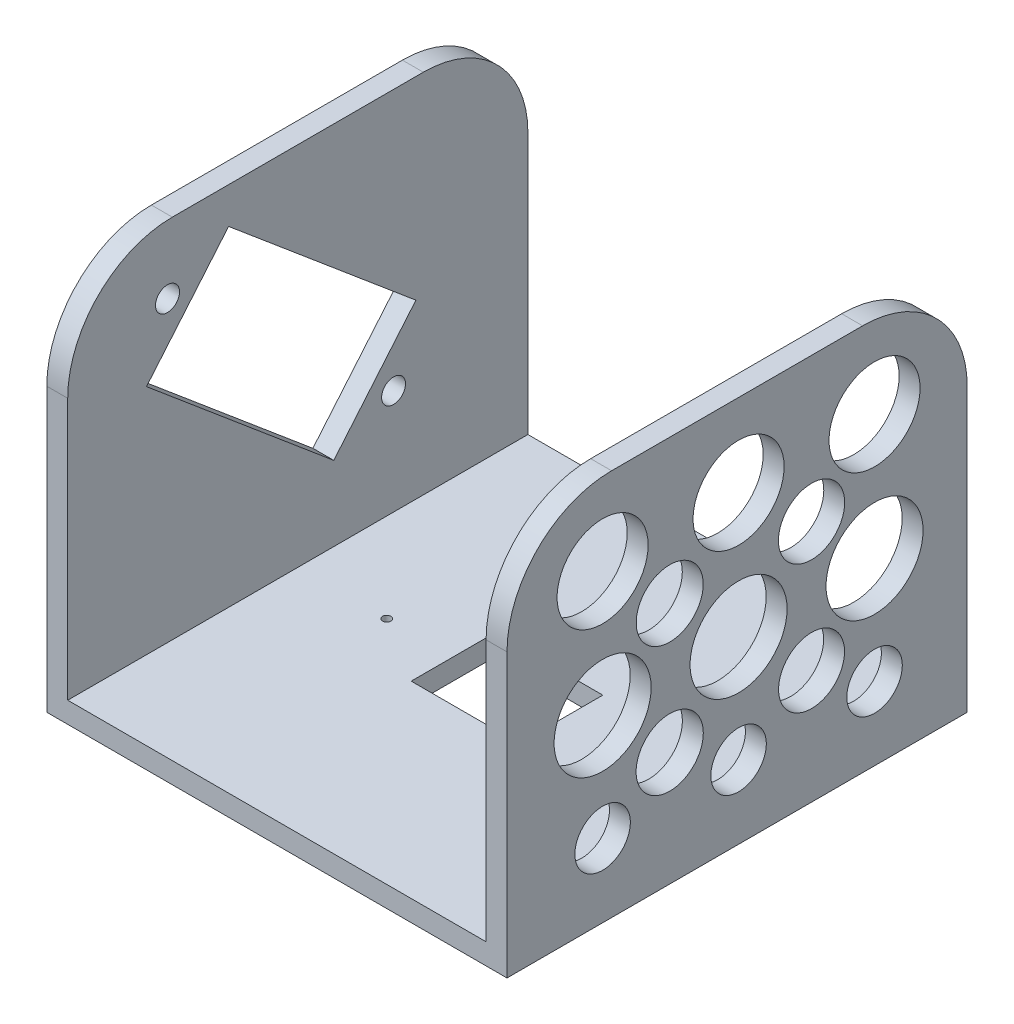
SolidWorks part; units mm, degrees
ref_plane "Front Plane" through (0, 0, 0) normal (0, 0, 1) x (1, 0, 0)
ref_plane "Top Plane" through (0, 0, 0) normal (0, 1, 0) x (1, 0, 0)
ref_plane "Right Plane" through (0, 0, 0) normal (1, 0, 0) x (0, 0, -1)
sketch "Sketch2" plane through (0, 0, 0) normal (0, 1, 0) x (1, 0, 0)
  line L1 (-22, 22) -> (22, 22)
  line L2 (-22, 22) -> (-22, -22)
  line L3 (-22, -22) -> (22, -22)
  line L4 (22, 22) -> (22, -22)
  line L5 (-22, 22) -> (22, -22) construction
  line L6 (-22, -22) -> (22, 22) construction
  point P0 (0, 0)
  dimension "D1" = 44
  dimension "D2" = 44
extrude "Boss-Extrude1" add sketch "Sketch2" along normal blind 2
sketch "Sketch4" plane through (0, 0, 0) normal (0, -1, 0) x (1, 0, 0)
  line L1 (-5.1594, 4) -> (5.1594, 4)
  line L2 (-5.1594, 4) -> (-5.1594, -4)
  line L3 (-5.1594, -4) -> (5.1594, -4)
  line L4 (5.1594, 4) -> (5.1594, -4)
  line L5 (-5.1594, 4) -> (5.1594, -4) construction
  line L6 (-5.1594, -4) -> (5.1594, 4) construction
  point P0 (0, 0)
  dimension "D1" = 10.3187
  dimension "D2" = 8
extrude "Cut-Extrude1" cut sketch "Sketch4" against normal through all
sketch "Sketch5" plane through (0, 0, 0) normal (0, -1, 0) x (1, 0, 0)
  circle A0 centre (-11.5, 0) radius 0.4
  dimension "D1" = 0.8
  dimension "D2" = 11.5
extrude "Cut-Extrude2" cut sketch "Sketch5" against normal blind 3
mirror "Mirror1" about plane through (0, 0, 0) normal (1, 0, 0) of "Cut-Extrude2"
sketch "Sketch8" plane through (0, 2, 0) normal (0, 1, 0) x (1, 0, 0)
  line L0 (-22, -22) -> (22, -22) construction
  line L1 (-22, 22) -> (-20, 22)
  line L2 (-22, 22) -> (-22, -22)
  line L3 (-22, -22) -> (-20, -22)
  line L4 (-20, 22) -> (-20, -22)
  dimension "D1" = 2
extrude "Boss-Extrude2" add sketch "Sketch8" along normal blind 35
mirror "Mirror2" about plane through (0, 0, 0) normal (1, 0, 0) of "Boss-Extrude2"
sketch "Sketch11" plane through (-22, 0, 0) normal (-1, 0, 0) x (0, 0, 1)
  line L0 (-22, 0) -> (22, 37) construction
  line L1 (-11.2906, 18.4782) -> (-3.4387, 9.1408)
  line L2 (-3.4387, 9.1408) -> (14.4708, 24.2011)
  line L3 (14.4708, 24.2011) -> (6.6188, 33.5385)
  line L4 (6.6188, 33.5385) -> (-11.2906, 18.4782)
  line L5 (-7.3647, 13.8095) -> (14.4708, 32.1711) construction
  line L6 (14.4708, 32.1711) -> (-10.1492, 11.468) construction
  line L7 (-8.5379, 11.3204) -> (-10.2465, 13.3522) construction
  circle A2 centre (-9.1537, 12.0539) radius 1.143
  circle A3 centre (12.4582, 30.4788) radius 1.15
  dimension "D4" = 2.286
  dimension "D6" = 2.3
  dimension "D7" = 2.5
  dimension "D1" = 23.4
  dimension "D2" = 12.2
  dimension "D3" = 14
  dimension "D5" = 2.5
extrude "Cut-Extrude3" cut sketch "Sketch11" against normal blind 10
fillet "Fillet1" radius 10 4 edges at (-21, 37, 22) (21, 37, -22) (21, 37, 22) (-21, 37, -22)
sketch "Sketch14" plane through (22, 0, 0) normal (1, 0, 0) x (0, 0, -1)
  circle A0 centre (-12.8589, 29.1086) radius 4.3514
  circle A1 centre (-12.8589, 17.1757) radius 4.6378
  circle A2 centre (-12.8589, 6.9986) radius 2.6537
extrude "Cut-Extrude5" cut sketch "Sketch14" against normal blind 10
pattern_linear "LPattern1" count 3 spacing 13 along (0, 0, -1) of "Cut-Extrude5"
sketch "Sketch16" plane through (22, 0, 0) normal (1, 0, 0) x (0, 0, -1)
  circle A0 centre (-6.4434, 10.902) radius 3.2122
  circle A1 centre (7.1184, 10.902) radius 3.1542
  circle A2 centre (7.1184, 23.2365) radius 3.1679
  circle A3 centre (-6.4434, 23.2365) radius 3.2034
extrude "Cut-Extrude6" cut sketch "Sketch16" against normal blind 10
